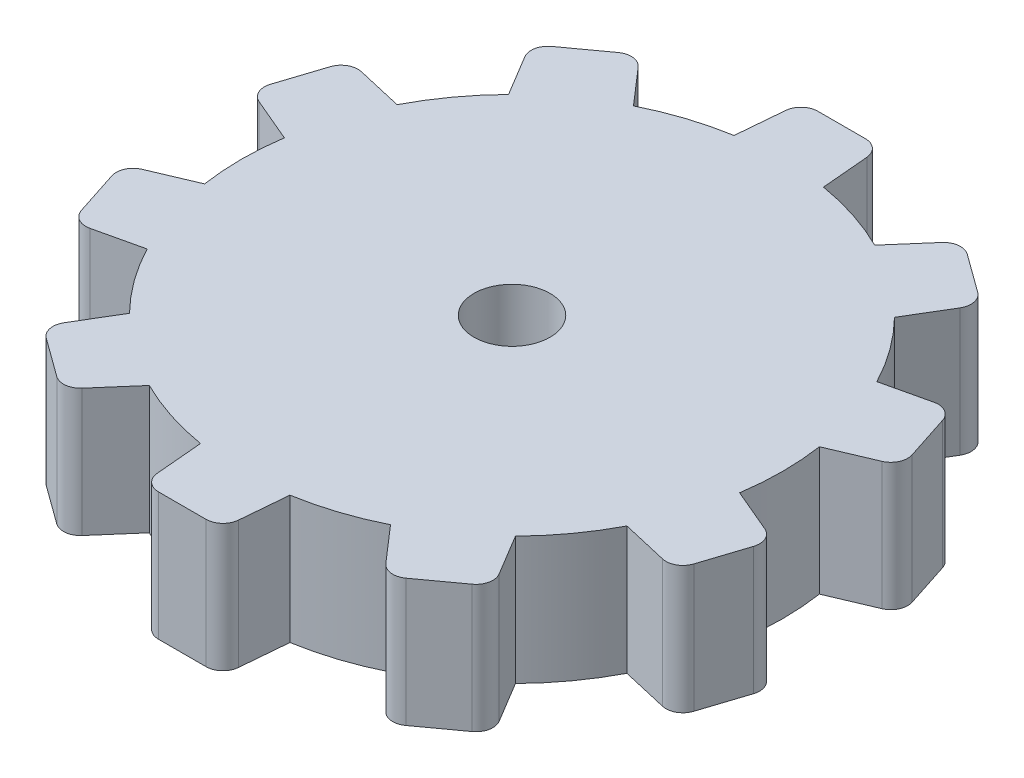
SolidWorks part; units mm, degrees
ref_plane "Front Plane" through (0, 0, 0) normal (0, 0, 1) x (1, 0, 0)
ref_plane "Top Plane" through (0, 0, 0) normal (0, 1, 0) x (1, 0, 0)
ref_plane "Right Plane" through (0, 0, 0) normal (1, 0, 0) x (0, 0, -1)
sketch "Sketch1" plane through (0, 0, 0) normal (0, 1, 0) x (1, 0, 0)
  circle A0 centre (0, 0) radius 16
  circle A1 centre (0, 0) radius 2.25
  dimension "D1" = 4.5
  dimension "D2" = 32
extrude "Boss-Extrude1" add sketch "Sketch1" along normal blind 7.55 contours A0 A1
sketch "Sketch2" plane through (0, 7.55, 0) normal (0, 1, 0) x (1, 0, 0)
  line L0 (0, 0) -> (0, 19.5) construction
  line L1 (-1.4037, 19.5) -> (1.4037, 19.5)
  line L2 (-7.7294, 16) -> (8.7664, 16) construction
  line L3 (-2.3999, 18.5872) -> (-2.6455, 15.7798)
  line L4 (2.3999, 18.5872) -> (2.6455, 15.7798)
  circle A0 centre (0, 0) radius 16 construction
  arc A1 (2.6455, 15.7798) -> (-2.6455, 15.7798) centre (0, 0) ccw
  arc A2 (-2.3999, 18.5872) -> (-1.4037, 19.5) centre (-1.4037, 18.5) cw
  arc A3 (1.4037, 19.5) -> (2.3999, 18.5872) centre (1.4037, 18.5) cw
  point P12 (-2.32, 19.5)
  point P15 (2.32, 19.5)
  dimension "D4" = 1
  dimension "D1" = 3.5
  dimension "D2" = 95
  dimension "D3" = 2.32
extrude "Boss-Extrude2" add sketch "Sketch2" against normal up to surface (7.55 mm away) up to face at (0, 0, 2.25)
pattern_circular "CirPattern1" count 10 over 360 about axis through (0, 0, 0) along (0, 1, 0) of "Boss-Extrude2"
